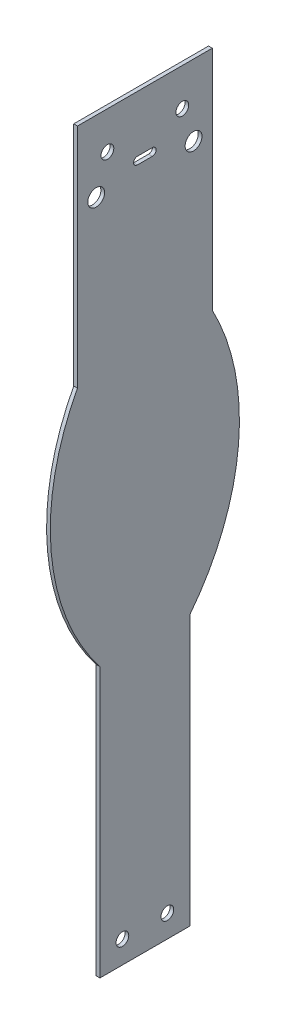
SolidWorks part; units mm, degrees
material "PVC 0.007 Plasticized"
ref_plane "Front Plane" through (0, 0, 0) normal (0, 0, 1) x (1, 0, 0)
ref_plane "Top Plane" through (0, 0, 0) normal (0, 1, 0) x (1, 0, 0)
ref_plane "Right Plane" through (0, 0, 0) normal (1, 0, 0) x (0, 0, -1)
sketch "Sketch1" plane through (0, 0, 0) normal (1, 0, 0) x (0, 0, -1)
  line L0 (12, -200) -> (12, -128)
  line L1 (-18, 0) -> (18, 0)
  line L2 (-18, 0) -> (-18, -200) construction
  line L3 (-18, -200) -> (18, -200) construction
  line L4 (18, 0) -> (18, -200) construction
  line L5 (-18, 0) -> (18, -200) construction
  line L6 (-18, -200) -> (18, 0) construction
  line L7 (-12, -200) -> (-12, -128)
  line L8 (12, -128) -> (-12, -128) construction
  line L9 (18, -60.6171) -> (-18, -60.6171) construction
  line L10 (18, 0) -> (18, -60.6171)
  line L11 (-18, 0) -> (-18, -60.6171)
  line L13 (12, -200) -> (-12, -200)
  arc A0 (18, -60.6171) -> (12, -128) centre (-36.7557, -89.7001) cw
  arc A1 (-18, -60.6171) -> (-12, -128) centre (36.7557, -89.7001) ccw
  point P4 (0, -100)
  point P5 (0, 0)
  point P10 (0, -128)
  point P15 (25, -95.199)
  dimension "D6" = 62
  dimension "D7" = 62
  dimension "D1" = 200
  dimension "D2" = 36
  dimension "D3" = 24
  dimension "D4" = 72
  dimension "D5" = 25
extrude "Boss-Extrude1" add sketch "Sketch1" along normal blind 1 contours L1 L10 A0 L0 L13 L7 A1 L11
hole_wizard "M3 Clearance Hole1" positions "Sketch6" profile "Sketch7" hole size "M3" standard "ISO" end condition through all
sketch "Sketch6" plane through (0, 0, 0) normal (-1, 0, 0) x (0, 0, 1)
  point P0 (10, -10)
  point P3 (-10, -10)
sketch "Sketch7" plane through (0, -10, 10) normal (0, 1, 0) x (0, 0, 1)
  line L0 (0, 0) -> (0, 1)
  line L1 (0, 1) -> (1.7, 1)
  line L2 (1.7, 1) -> (1.7, 0)
  line L5 (1.7, 0) -> (0, 0)
  line L11 (0, -6.35) -> (0, 107.95) construction
  dimension "Thru Hole Dia." = 3.4
  dimension "Thru Hole Depth" = 1
hole_wizard "M4 Clearance Hole1" positions "Sketch8" profile "Sketch9" hole size "M4" standard "ISO" end condition through all
sketch "Sketch8" plane through (0, 0, 0) normal (-1, 0, 0) x (0, 0, 1)
  point P4 (-13, -19)
  point P7 (13, -19)
sketch "Sketch9" plane through (0, -19, -13) normal (0, 1, 0) x (0, 0, 1)
  line L0 (0, 0) -> (0, 1)
  line L1 (0, 1) -> (2.25, 1)
  line L2 (2.25, 1) -> (2.25, 0)
  line L5 (2.25, 0) -> (0, 0)
  line L11 (0, -6.35) -> (0, 107.95) construction
  dimension "Thru Hole Dia." = 4.5
  dimension "Thru Hole Depth" = 1
sketch "Sketch10" plane through (1, 0, 0) normal (1, 0, 0) x (0, 0, -1)
  line L0 (-2, -16) -> (2, -16) construction
  line L1 (-2, -15) -> (2, -15)
  line L2 (-2, -17) -> (2, -17)
  line L3 (-18, 0) -> (18, 0) construction
  arc A0 (-2, -15) -> (-2, -17) centre (-2, -16) ccw
  arc A1 (2, -17) -> (2, -15) centre (2, -16) ccw
  point P2 (0, -16)
  dimension "D2" = 1
  dimension "D1" = 4
  dimension "D3" = 16
extrude "Cut-Extrude1" cut sketch "Sketch10" against normal through all
hole_wizard "M3 Clearance Hole2" positions "Sketch12" profile "Sketch11" hole size "M3" standard "ISO" end condition through all
sketch "Sketch12" plane through (1, 0, 0) normal (1, 0, 0) x (0, 0, -1)
  line L1 (12, -200) -> (-12, -200) construction
  point P0 (-6, -194)
  point P2 (6, -194)
  dimension "D1" = 12
  dimension "D2" = 6
  dimension "D3" = 6
sketch "Sketch11" plane through (1, -194, 6) normal (0, 1, 0) x (0, 0, -1)
  line L0 (0, 0) -> (0, 1)
  line L1 (0, 1) -> (1.7, 1)
  line L2 (1.7, 1) -> (1.7, 0)
  line L5 (1.7, 0) -> (0, 0)
  line L11 (0, -6.35) -> (0, 107.95) construction
  dimension "Thru Hole Dia." = 3.4
  dimension "Thru Hole Depth" = 1
